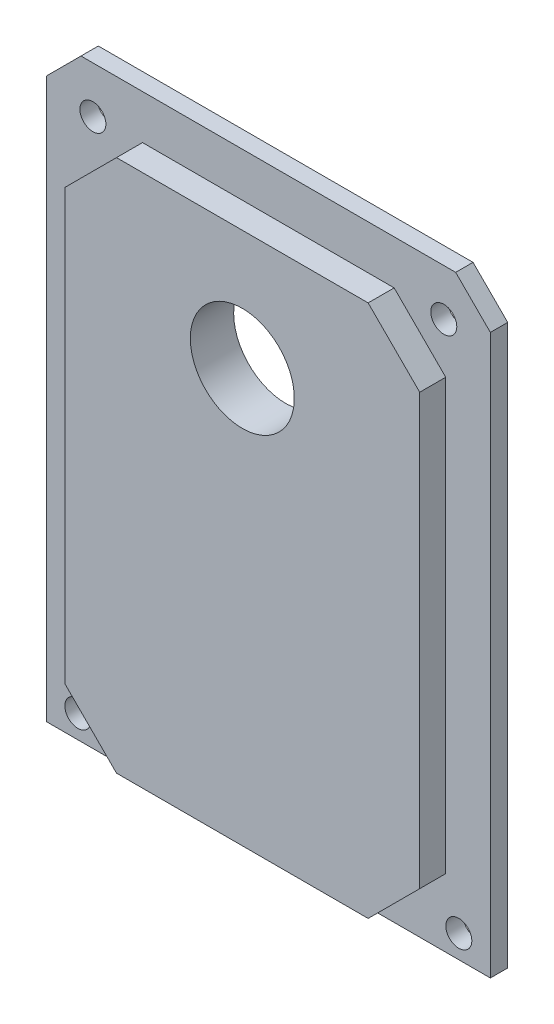
SolidWorks part; units mm, degrees
ref_plane "Front Plane" through (0, 0, 0) normal (0, 0, 1) x (1, 0, 0)
ref_plane "Top Plane" through (0, 0, 0) normal (0, 1, 0) x (1, 0, 0)
ref_plane "Right Plane" through (0, 0, 0) normal (1, 0, 0) x (0, 0, -1)
sketch "Sketch1" plane through (0, 0, 0) normal (0, 0, 1) x (1, 0, 0)
  line L1 (-25.615, -34.25) -> (25.615, -34.25)
  line L2 (-25.615, -34.25) -> (-25.615, 34.25)
  line L3 (-25.615, 34.25) -> (25.615, 34.25)
  line L4 (25.615, -34.25) -> (25.615, 34.25)
  line L5 (-25.615, -34.25) -> (25.615, 34.25) construction
  line L6 (-25.615, 34.25) -> (25.615, -34.25) construction
  point P0 (0, 0)
  dimension "D1" = 68.5
  dimension "D2" = 51.23
extrude "Boss-Extrude1" add sketch "Sketch1" along normal blind 2
chamfer "Chamfer1" distance 4 angle 45 2 edges at (25.615, 34.25, 1) (-25.615, 34.25, 1)
sketch "Sketch3" plane through (0, 0, 2) normal (0, 0, 1) x (1, 0, 0)
  line L5 (0, -34.25) -> (0, -1.6) construction
  line L6 (-25.615, -34.25) -> (25.615, -34.25) construction
  line L9 (-25.615, 30.25) -> (-25.615, -34.25) construction
  line L10 (-20.465, -32.35) -> (20.465, -32.35)
  line L11 (-20.465, -32.35) -> (-20.465, 29.15)
  line L12 (-20.465, 29.15) -> (20.465, 29.15)
  line L13 (20.465, -32.35) -> (20.465, 29.15)
  line L14 (-20.465, -32.35) -> (20.465, 29.15) construction
  line L15 (-20.465, 29.15) -> (20.465, -32.35) construction
  line L16 (25.615, -34.25) -> (25.615, 30.25) construction
  line L17 (21.615, 34.25) -> (-21.615, 34.25) construction
  point P0 (0, 0)
  dimension "D1" = 5.15
  dimension "D2" = 5.15
  dimension "D3" = 5.1
  dimension "D4" = 61.5
extrude "Boss-Extrude3" add sketch "Sketch3" along normal blind 3
chamfer "Chamfer2" distance 5.95 angle 45 4 edges at (20.465, -32.35, 3.5) (-20.465, -32.35, 3.5) (-20.465, 29.15, 3.5) (20.465, 29.15, 3.5)
sketch "Sketch4" plane through (0, 0, 2) normal (0, 0, 1) x (1, 0, 0)
  line L0 (-25.615, -34.25) -> (-21.9744, -31.605) construction
  line L1 (-25.615, -34.25) -> (25.615, -34.25) construction
  line L2 (25.615, -34.25) -> (21.9744, -31.605) construction
  line L3 (-23.615, 32.25) -> (-20.2421, 28.8771) construction
  line L4 (-21.615, 34.25) -> (-25.615, 30.25) construction
  line L5 (23.615, 32.25) -> (20.2421, 28.8771) construction
  line L6 (25.615, 30.25) -> (21.615, 34.25) construction
  circle A0 centre (-20.2421, 28.8771) radius 1.5
  circle A1 centre (20.2421, 28.8771) radius 1.5
  circle A2 centre (21.9744, -31.605) radius 1.5
  circle A3 centre (-21.9744, -31.605) radius 1.5
  dimension "D4" = 3
  dimension "D1" = 36
  dimension "D2" = 4.5
  dimension "D3" = 36
extrude "Cut-Extrude1" cut sketch "Sketch4" against normal through all
sketch "Sketch5" plane through (0, 0, 0) normal (0, 0, -1) x (-1, 0, 0)
  line L0 (0, -34.25) -> (0, 15.35) construction
  line L1 (25.615, -34.25) -> (-25.615, -34.25) construction
  circle A0 centre (0, 15.35) radius 6
  dimension "D1" = 12
  dimension "D2" = 49.6
extrude "Cut-Extrude2" cut sketch "Sketch5" against normal through all
